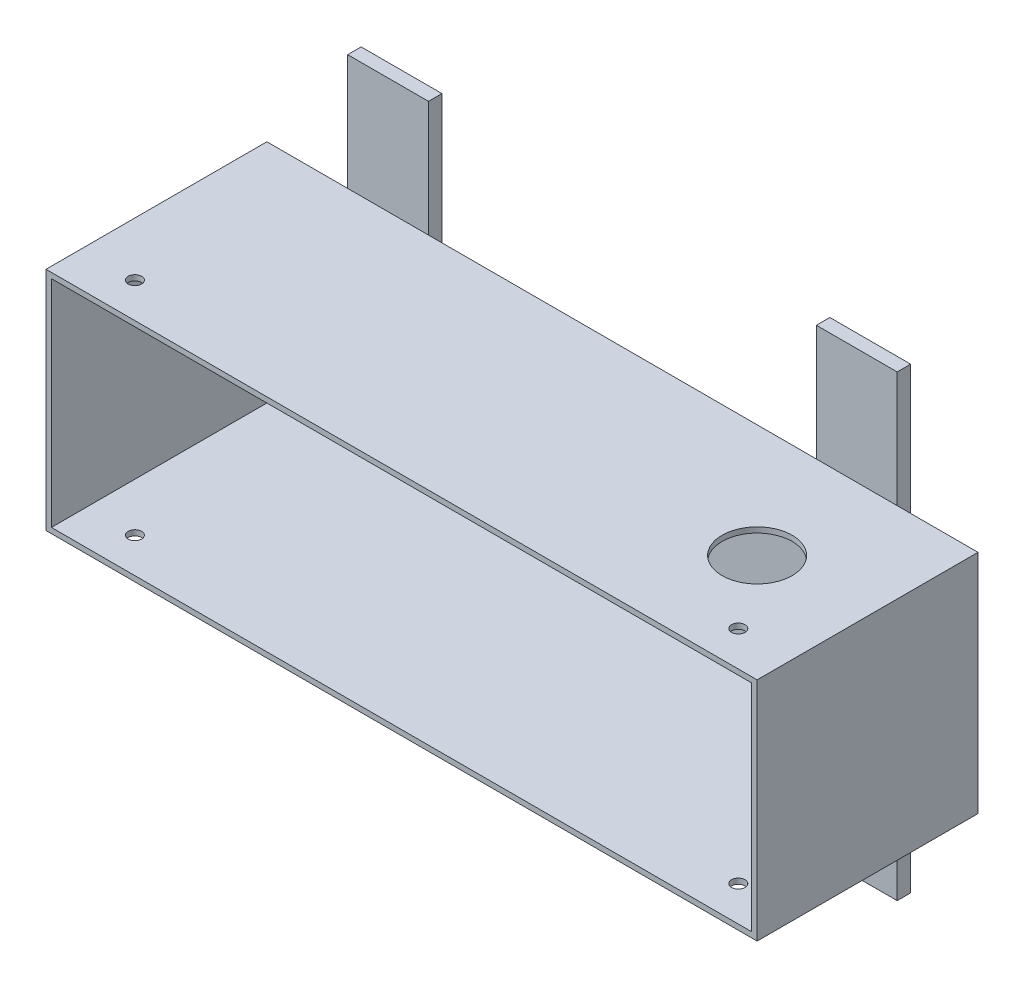
SolidWorks part; units mm, degrees
ref_plane "Front Plane" through (0, 0, 0) normal (0, 0, 1) x (1, 0, 0)
ref_plane "Top Plane" through (0, 0, 0) normal (0, 1, 0) x (1, 0, 0)
ref_plane "Right Plane" through (0, 0, 0) normal (1, 0, 0) x (0, 0, -1)
sketch "Sketch1" plane through (0, 0, 0) normal (0, 0, 1) x (1, 0, 0)
  line L1 (0, 0) -> (260, 0)
  line L2 (0, 0) -> (0, 80)
  line L3 (0, 80) -> (260, 80)
  line L4 (260, 0) -> (260, 80)
  dimension "D1" = 260
  dimension "D2" = 80
extrude "Boss-Extrude1" add sketch "Sketch1" along normal blind 80
shell "Shell1" thickness 2
sketch "Sketch3" plane through (0, 0, -2) normal (0, 0, -1) x (-1, 0, 0)
  line L0 (-262, -2) -> (-262, 82) construction
  line L1 (-232, 125) -> (-202, 125)
  line L2 (-232, 125) -> (-232, -45)
  line L3 (-232, -45) -> (-202, -45)
  line L4 (-202, 125) -> (-202, -45)
  line L9 (-130, 124.4166) -> (-130, -41.0679) construction
  line L10 (-58, 125) -> (-58, -45)
  line L11 (-28, -45) -> (-58, -45)
  line L12 (-28, 125) -> (-28, -45)
  line L13 (-28, 125) -> (-58, 125)
  line L14 (2, 82) -> (2, -2) construction
  point P11 (-262, 40)
  point P12 (-232, 40)
  dimension "D1" = 30
  dimension "D2" = 30
  dimension "D3" = 170
  dimension "D4" = 30
extrude "Boss-Extrude2" add sketch "Sketch3" along normal blind 5
sketch "Sketch4" plane through (0, 0, -7) normal (0, 0, -1) x (-1, 0, 0)
  line L0 (-262, 82) -> (-232, 82) construction
  line L1 (-232, -2) -> (-262, -2) construction
  line L4 (-202, 125) -> (-232, 125) construction
  circle A0 centre (-217, 66) radius 5
  circle A1 centre (-217, 14) radius 5
  point P11 (-217, 125)
  dimension "D1" = 10
  dimension "D2" = 10
  dimension "D4" = 16
  dimension "D3" = 16
extrude "Cut-Extrude3" cut sketch "Sketch4" against normal up to surface (7 mm away) up to face at (130, 40, 0)
ref_plane "Plane1" through (130, 0, 0) normal (1, 0, 0) x (0, 0, -1)
mirror "Mirror1" about plane through (130, 0, 0) normal (1, 0, 0) of "Cut-Extrude3"
sketch "Sketch6" plane through (0, 82, 0) normal (0, 1, 0) x (1, 0, 0)
  line L0 (262, -80) -> (262, 2) construction
  line L1 (262, -80) -> (-2, -80) construction
  circle A0 centre (222, -40) radius 13
  dimension "D1" = 26
  dimension "D2" = 40
  dimension "D3" = 40
extrude "Cut-Extrude4" cut sketch "Sketch6" against normal up to surface (2 mm away) up to face at (130, 80, 40)
sketch "Sketch7" plane through (0, 82, 0) normal (0, 1, 0) x (1, 0, 0)
  line L0 (262, -80) -> (-2, -80) construction
  line L1 (262, -80) -> (262, 2) construction
  line L2 (-2, -80) -> (-2, 2) construction
  circle A0 centre (18, -67) radius 2.5
  circle A1 centre (242, -67) radius 2.5
  dimension "D1" = 5
  dimension "D2" = 13
  dimension "D3" = 20
  dimension "D4" = 5
  dimension "D5" = 13
  dimension "D6" = 20
extrude "Cut-Extrude5" cut sketch "Sketch7" against normal up to surface (82 mm away)
ref_plane "Plane2" through (0, 40, 0) normal (0, -1, 0) x (-1, 0, 0)
mirror "Mirror2" about plane through (0, 40, 0) normal (0, -1, 0) of "Cut-Extrude5"
